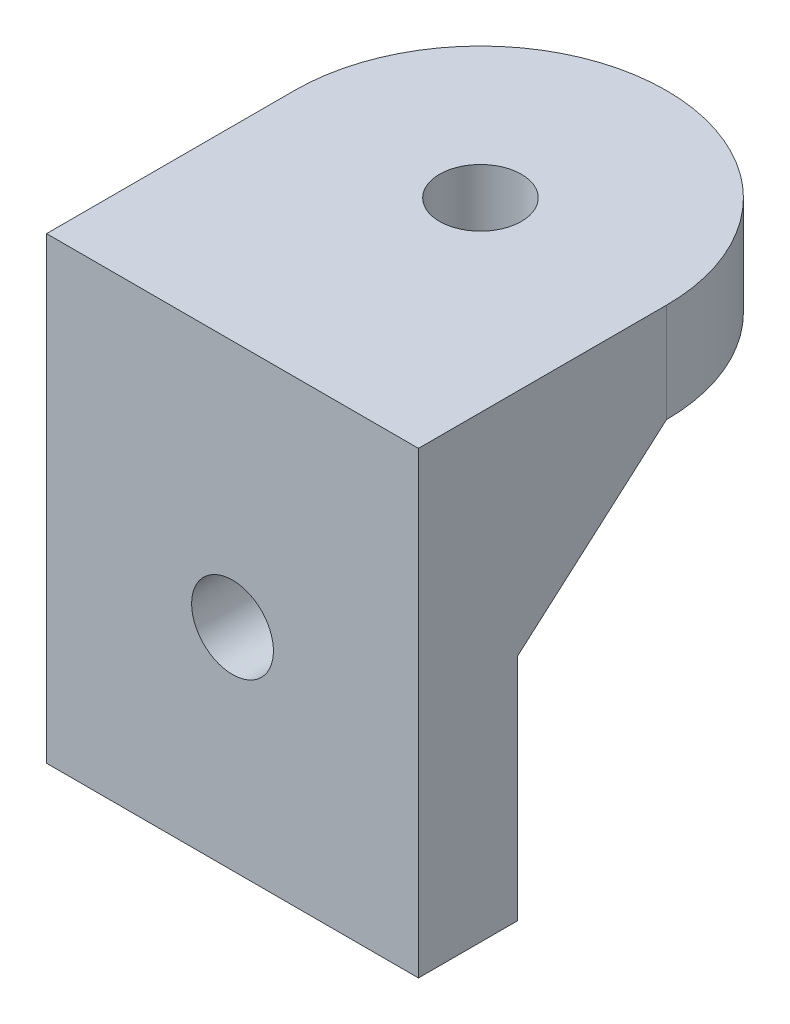
SolidWorks part; units mm, degrees
ref_plane "前视基准面" through (0, 0, 0) normal (0, 0, 1) x (1, 0, 0)
ref_plane "上视基准面" through (0, 0, 0) normal (0, 1, 0) x (1, 0, 0)
ref_plane "右视基准面" through (0, 0, 0) normal (1, 0, 0) x (0, 0, -1)
sketch "草图1" plane through (0, 0, 0) normal (0, 0, 1) x (1, 0, 0)
  line L1 (-15, -18.5) -> (15, -18.5)
  line L2 (-15, -18.5) -> (-15, 18.5)
  line L3 (-15, 18.5) -> (15, 18.5)
  line L4 (15, -18.5) -> (15, 18.5)
  line L5 (-15, -18.5) -> (15, 18.5) construction
  line L6 (-15, 18.5) -> (15, -18.5) construction
  point P0 (0, 0)
  dimension "D1" = 30
  dimension "D2" = 37
extrude "凸台-拉伸1" add sketch "草图1" along normal blind 8
sketch "草图2" plane through (0, 18.5, 0) normal (0, 1, 0) x (1, 0, 0)
  line L0 (-15, -8) -> (15, -8)
  line L1 (-15, -8) -> (-15, 12)
  line L2 (15, -8) -> (15, 12)
  arc A0 (-15, 12) -> (15, 12) centre (0, 12) cw
  dimension "D1" = 35
extrude "凸台-拉伸2" add sketch "草图2" against normal blind 8
sketch "草图5" plane through (15, 0, 0) normal (1, 0, 0) x (0, 0, -1)
  line L0 (12, 10.5) -> (0, 10.5)
  line L1 (0, 10.5) -> (0, 0)
  line L2 (0, 0) -> (12, 10.5)
extrude "凸台-拉伸3" add sketch "草图5" against normal blind 3.8
mirror "镜向1" about plane through (0, 0, 0) normal (1, 0, 0) of "凸台-拉伸3"
hole_wizard "M6 平锥沉头螺钉的锥形沉头孔1" positions "草图7" profile "草图6" countersink size "M6" standard "JIS" end condition through all
sketch "草图7" plane through (0, 0, 0) normal (0, 0, -1) x (-1, 0, 0)
  line L0 (-15, 18.5) -> (15, 18.5) construction
  line L1 (15, -18.5) -> (-15, -18.5) construction
  point P0 (0, -1.5)
  point P10 (0, -18.5)
  dimension "D1" = 20
sketch "草图6" plane through (0, -1.5, 0) normal (1, 0, 0) x (0, 1, 0)
  line L0 (0, 0) -> (0, 8)
  line L1 (0, 8) -> (3.3, 8)
  line L2 (3.3, 8) -> (3.3, 3)
  line L3 (3.3, 3) -> (6.3, 0)
  line L5 (6.3, 0) -> (0, 0)
  line L6 (-3.3, 3) -> (-6.3, 0) construction
  line L11 (0, -6.35) -> (0, 107.95) construction
  dimension "通孔孔直径" = 6.6
  dimension "通孔孔深度" = 8
  dimension "近端锥形沉头孔直径" = 12.6
  dimension "近端锥形沉头孔角度" = 90
hole_wizard "M6 平锥沉头螺钉的锥形沉头孔2" positions "草图9" profile "草图8" countersink size "M6" standard "JIS" end condition through all
sketch "草图9" plane through (0, 10.5, 0) normal (0, -1, 0) x (1, 0, 0)
  line L0 (-15, 8) -> (15, 8) construction
  arc A0 (-15, -12) -> (15, -12) centre (0, -12) ccw construction
  arc A1 (-15, -12) -> (15, -12) centre (0, -12) ccw
  point P0 (0, -12)
  point P8 (0, 8)
  dimension "D1" = 20
sketch "草图8" plane through (0, 10.5, -12) normal (1, 0, 0) x (0, 0, -1)
  line L0 (0, 0) -> (0, 8)
  line L1 (0, 8) -> (3.3, 8)
  line L2 (3.3, 8) -> (3.3, 3)
  line L3 (3.3, 3) -> (6.3, 0)
  line L5 (6.3, 0) -> (0, 0)
  line L6 (-3.3, 3) -> (-6.3, 0) construction
  line L11 (0, -6.35) -> (0, 107.95) construction
  dimension "通孔孔直径" = 6.6
  dimension "通孔孔深度" = 8
  dimension "近端锥形沉头孔直径" = 12.6
  dimension "近端锥形沉头孔角度" = 90
